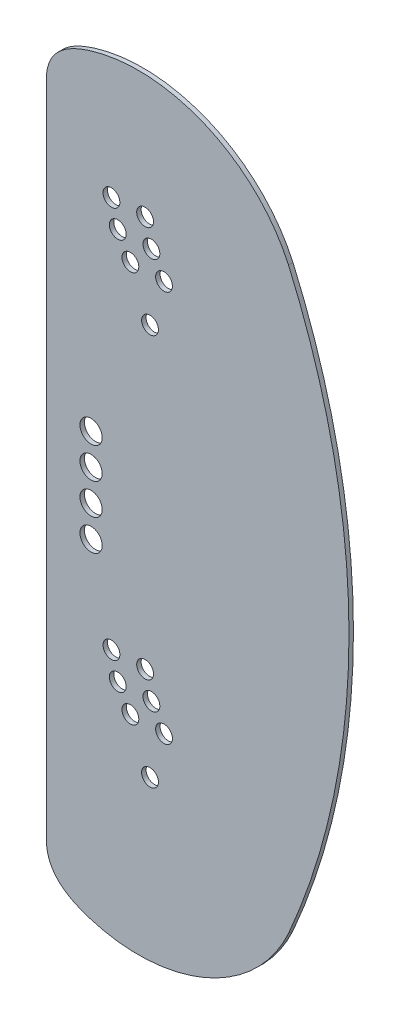
SolidWorks part; units mm, degrees
material "Acrylic (Medium-high impact)"
ref_plane "Front Plane" through (0, 0, 0) normal (0, 0, 1) x (1, 0, 0)
ref_plane "Top Plane" through (0, 0, 0) normal (0, 1, 0) x (1, 0, 0)
ref_plane "Right Plane" through (0, 0, 0) normal (1, 0, 0) x (0, 0, -1)
sketch "Sketch1" plane through (0, 0, 0) normal (0, 0, 1) x (1, 0, 0)
  line L95 (1361.0966, 1948.8635) -> (1361.0966, 996.3635)
  arc A0 (1706.2361, 1059.6777) -> (1706.2361, 1885.5492) centre (761.2616, 1472.6135) ccw
  circle A3 centre (1510.6649, 1248.8146) radius 12
  circle A7 centre (1462.6649, 1248.8145) radius 12
  circle A9 centre (1508.6644, 1153.8145) radius 12
  circle A19 centre (1508.6644, 1712.6145) radius 12
  circle A20 centre (1453.6649, 1283.8145) radius 12
  circle A21 centre (1528.6649, 1217.5646) radius 12
  circle A24 centre (1480.665, 1217.5646) radius 12
  circle A28 centre (1501.6649, 1283.8145) radius 12
  circle A29 centre (1424.5966, 1539.2885) radius 15.875
  circle A30 centre (1424.5966, 1494.8385) radius 15.875
  circle A31 centre (1424.5966, 1450.3885) radius 15.875
  circle A32 centre (1424.5966, 1405.9385) radius 15.875
  circle A40 centre (1501.6649, 1842.6145) radius 12
  circle A41 centre (1510.6649, 1807.6146) radius 12
  circle A42 centre (1528.6649, 1776.3646) radius 12
  circle A43 centre (1462.665, 1807.6146) radius 12
  circle A44 centre (1480.6649, 1776.3646) radius 12
  circle A45 centre (1453.665, 1842.6145) radius 12
  circle A46 centre (1508.6644, 1712.6145) radius 12
  spline S1 degree 3 poles (1361.0966, 996.3635) (1364.4008, 961.2038) (1498.6132, 888.7647) (1658.3076, 954.5721) (1706.2361, 1059.6777) knots 0 0 0 0 0.219674 1 1 1 1
  spline S2 degree 3 poles (1361.0966, 1948.8635) (1364.4008, 1984.0232) (1498.6132, 2056.4623) (1658.3076, 1990.6549) (1706.2361, 1885.5492) knots 0 0 0 0 0.219674 1 1 1 1
extrude "Boss-Extrude1" add sketch "Sketch1" along normal blind 6.35 contours S2 L95 S1 A0 A45 A44 A43 A42 A41 A40 A32 A31 A30 A29 A28 A24 A21 A20 A19 A9 A7 A3
